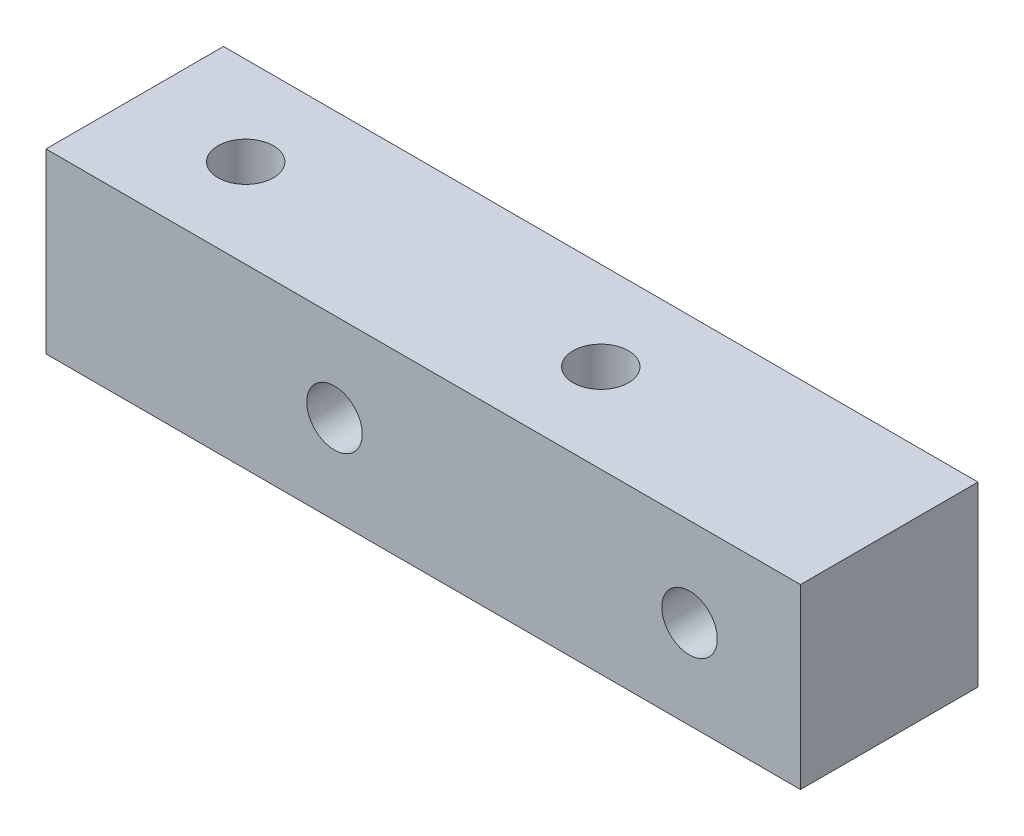
SolidWorks part; units mm, degrees
material "6061 合金"
ref_plane "前视基准面" through (0, 0, 0) normal (0, 0, 1) x (1, 0, 0)
ref_plane "上视基准面" through (0, 0, 0) normal (0, 1, 0) x (1, 0, 0)
ref_plane "右视基准面" through (0, 0, 0) normal (1, 0, 0) x (0, 0, -1)
sketch "草图1" plane through (0, 0, 0) normal (0, 0, 1) x (1, 0, 0)
  line L1 (17, -4) -> (-17, -4)
  line L2 (17, -4) -> (17, 4)
  line L3 (17, 4) -> (-17, 4)
  line L4 (-17, -4) -> (-17, 4)
  line L5 (17, -4) -> (-17, 4) construction
  line L6 (17, 4) -> (-17, -4) construction
  point P0 (0, 0)
  dimension "D1" = 34
  dimension "D2" = 8
extrude "凸台-拉伸1" add sketch "草图1" along normal blind 8
sketch "草图2" plane through (0, 0, 0) normal (0, 0, -1) x (-1, 0, 0)
  line L0 (-17, -4) -> (-17, 4) construction
  point P0 (-12, 0)
  point P1 (4, 0)
  dimension "D1" = 5
  dimension "D2" = 16
sketch "草图3" plane through (0, 4, 0) normal (0, 1, 0) x (1, 0, 0)
  line L0 (-17, -8) -> (-17, 0) construction
  point P0 (-12, -4)
  point P1 (4, -4)
  dimension "D1" = 5
  dimension "D2" = 16
hole_wizard "M3 螺纹孔的螺纹孔钻头1" positions "3D草图1" profile "草图4" hole size "M3" standard "DIN" end condition through all
sketch3d "3D草图1"
  point P0 (4, 4, 4)
  point P3 (-12, 4, 4)
  point P6 (-4, 0, 0)
  point P9 (12, 0, 0)
sketch "草图4" plane through (4, 4, 4) normal (1, 0, 0) x (0, 0, 1)
  line L0 (0, 0) -> (0, 8)
  line L1 (0, 8) -> (1.25, 8)
  line L2 (1.25, 8) -> (1.25, 0)
  line L5 (1.25, 0) -> (0, 0)
  line L11 (0, -6.35) -> (0, 107.95) construction
  dimension "通孔孔直径" = 2.5
  dimension "通孔孔深度" = 8
